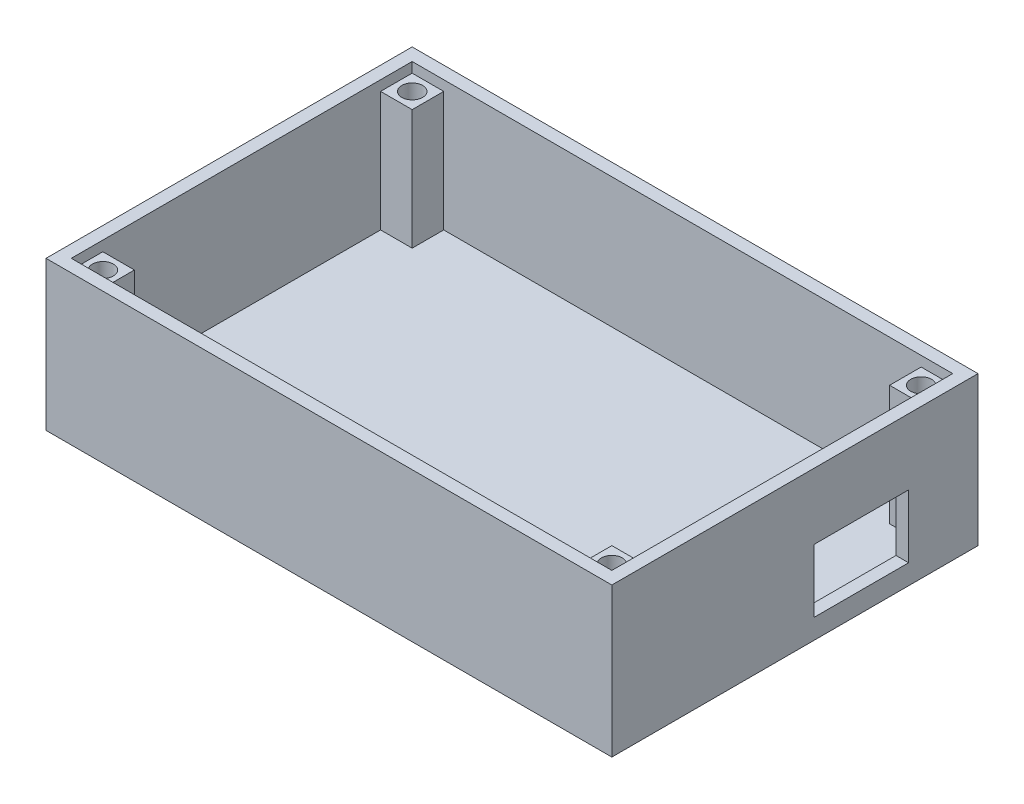
SolidWorks part; units mm, degrees
ref_plane "Front Plane" through (0, 0, 0) normal (0, 0, 1) x (1, 0, 0)
ref_plane "Top Plane" through (0, 0, 0) normal (0, 1, 0) x (1, 0, 0)
ref_plane "Right Plane" through (0, 0, 0) normal (1, 0, 0) x (0, 0, -1)
sketch "Sketch1" plane through (0, 0, 0) normal (0, 1, 0) x (1, 0, 0)
  line L1 (-42.8, -26.99) -> (42.8, -26.99)
  line L2 (-42.8, -26.99) -> (-42.8, 26.99)
  line L3 (-42.8, 26.99) -> (42.8, 26.99)
  line L4 (42.8, -26.99) -> (42.8, 26.99)
  line L5 (-42.8, -26.99) -> (42.8, 26.99) construction
  line L6 (-42.8, 26.99) -> (42.8, -26.99) construction
  line L7 (-44.8, -28.99) -> (44.8, -28.99)
  line L8 (-44.8, -28.99) -> (-44.8, 28.99)
  line L9 (-44.8, 28.99) -> (44.8, 28.99)
  line L10 (44.8, -28.99) -> (44.8, 28.99)
  line L11 (-44.8, -28.99) -> (44.8, 28.99) construction
  line L12 (-44.8, 28.99) -> (44.8, -28.99) construction
  point P0 (0, 0)
  point P6 (0, 0)
  dimension "D1" = 85.6
  dimension "D2" = 53.98
  dimension "D3" = 89.6
  dimension "D4" = 57.98
extrude "Boss-Extrude1" add sketch "Sketch1" along normal blind 20.6
sketch "Sketch2" plane through (0, 0, 0) normal (0, -1, 0) x (1, 0, 0)
  line L1 (-44.8, -28.99) -> (44.8, -28.99)
  line L2 (-44.8, -28.99) -> (-44.8, 28.99)
  line L3 (-44.8, 28.99) -> (44.8, 28.99)
  line L4 (44.8, -28.99) -> (44.8, 28.99)
  line L5 (-44.8, -28.99) -> (44.8, 28.99) construction
  line L6 (-44.8, 28.99) -> (44.8, -28.99) construction
  point P1 (0, 0)
extrude "Boss-Extrude2" add sketch "Sketch2" along normal blind 3
sketch "Sketch3" plane through (0, 0, 0) normal (0, 1, 0) x (1, 0, 0)
  line L1 (42.8, 26.99) -> (37.8, 26.99)
  line L2 (42.8, 26.99) -> (42.8, 21.99)
  line L3 (42.8, 21.99) -> (37.8, 21.99)
  line L4 (37.8, 26.99) -> (37.8, 21.99)
  line L5 (-42.8, 26.99) -> (-37.8, 26.99)
  line L6 (-42.8, 26.99) -> (-42.8, 21.99)
  line L7 (-42.8, 21.99) -> (-37.8, 21.99)
  line L8 (-37.8, 26.99) -> (-37.8, 21.99)
  line L9 (-42.8, -26.99) -> (-37.8, -26.99)
  line L10 (-42.8, -26.99) -> (-42.8, -21.99)
  line L11 (-42.8, -21.99) -> (-37.8, -21.99)
  line L12 (-37.8, -26.99) -> (-37.8, -21.99)
  line L13 (42.8, -26.99) -> (37.8, -26.99)
  line L14 (42.8, -26.99) -> (42.8, -21.99)
  line L15 (42.8, -21.99) -> (37.8, -21.99)
  line L16 (37.8, -26.99) -> (37.8, -21.99)
  dimension "D1" = 5
  dimension "D2" = 5
  dimension "D3" = 5
  dimension "D4" = 5
  dimension "D5" = 5
  dimension "D6" = 5
  dimension "D7" = 5
  dimension "D8" = 5
extrude "Boss-Extrude3" add sketch "Sketch3" along normal blind 19 separate body
sketch "Sketch4" plane through (0, 19, 0) normal (0, 1, 0) x (1, 0, 0)
  circle A0 centre (-40.2908, 24.4892) radius 1.65
  circle A1 centre (40.299, 24.4902) radius 1.65
  circle A2 centre (40.299, -24.4951) radius 1.65
  circle A3 centre (-40.2908, -24.4951) radius 1.65
extrude "Cut-Extrude2" cut sketch "Sketch4" against normal blind 4 contours A3 | A2 | A1 | A0
sketch "Sketch5" plane through (44.8, 0, 0) normal (1, 0, 0) x (0, 0, -1)
  line L1 (2.9999, 10.1519) -> (17.9999, 10.1519)
  line L2 (2.9999, 10.1519) -> (2.9999, 0.1519)
  line L3 (2.9999, 0.1519) -> (17.9999, 0.1519)
  line L4 (17.9999, 10.1519) -> (17.9999, 0.1519)
  dimension "D1" = 15
  dimension "D2" = 10
extrude "Cut-Extrude3" cut sketch "Sketch5" against normal blind 4
